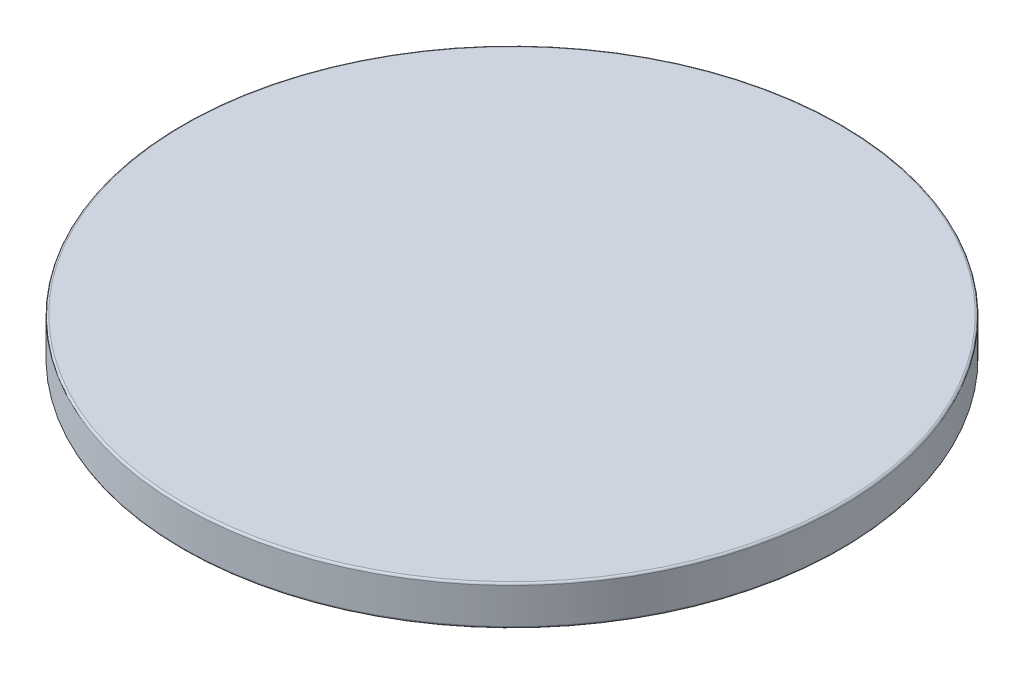
SolidWorks part; units mm, degrees
material "AISI 304"
ref_plane "Front Plane" through (0, 0, 0) normal (0, 0, 1) x (1, 0, 0)
ref_plane "Top Plane" through (0, 0, 0) normal (0, 1, 0) x (1, 0, 0)
ref_plane "Right Plane" through (0, 0, 0) normal (1, 0, 0) x (0, 0, -1)
sketch "Sketch1" plane through (0, 0, 0) normal (1, 0, 0) x (0, 0, -1)
  line L0 (0, 14.4131) -> (0, -9.9582) construction
  line L1 (0, 0.75) -> (-12.425, 0.75)
  line L2 (-12.5, 0.675) -> (-12.5, -0.675)
  line L3 (0, -0.75) -> (-12.425, -0.75)
  line L4 (-12.5, 0) -> (2.9197, 0) construction
  line L5 (0, 0.75) -> (0, -0.75)
  arc A0 (-12.425, 0.75) -> (-12.5, 0.675) centre (-12.425, 0.675) ccw
  arc A1 (-12.425, -0.75) -> (-12.5, -0.675) centre (-12.425, -0.675) cw
  point P7 (-12.425, 0.7192)
  point P8 (-12.5, 0.675)
  dimension "D1" = 25
  dimension "D3" = 0.075
  dimension "D2" = 0.75
revolve "Revolve1" add sketch "Sketch1" angle 360 about L0
